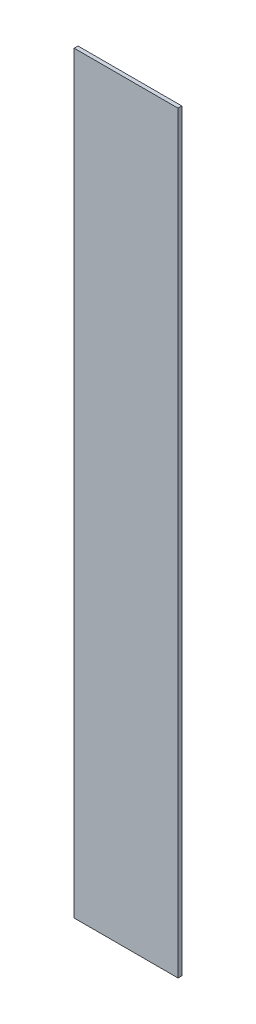
SolidWorks part; units mm, degrees
ref_plane "Front" through (0, 0, 0) normal (0, 0, 1) x (1, 0, 0)
ref_plane "Top" through (0, 0, 0) normal (0, 1, 0) x (1, 0, 0)
ref_plane "Right" through (0, 0, 0) normal (1, 0, 0) x (0, 0, -1)
sketch "Sketch1" plane through (0, 0, 0) normal (0, 0, 1) x (1, 0, 0)
  line L5 (-171.45, -1244.6) -> (171.45, -1244.6)
  line L6 (-171.45, -1244.6) -> (-171.45, 1244.6)
  line L7 (-171.45, 1244.6) -> (171.45, 1244.6)
  line L8 (171.45, -1244.6) -> (171.45, 1244.6)
  line L9 (-171.45, -1244.6) -> (171.45, 1244.6) construction
  line L10 (-171.45, 1244.6) -> (171.45, -1244.6) construction
  point P4 (0, 0)
  dimension "D1" = 342.9
  dimension "D2" = 2489.2
extrude "Boss-Extrude1" add sketch "Sketch1" along normal blind 12.7
